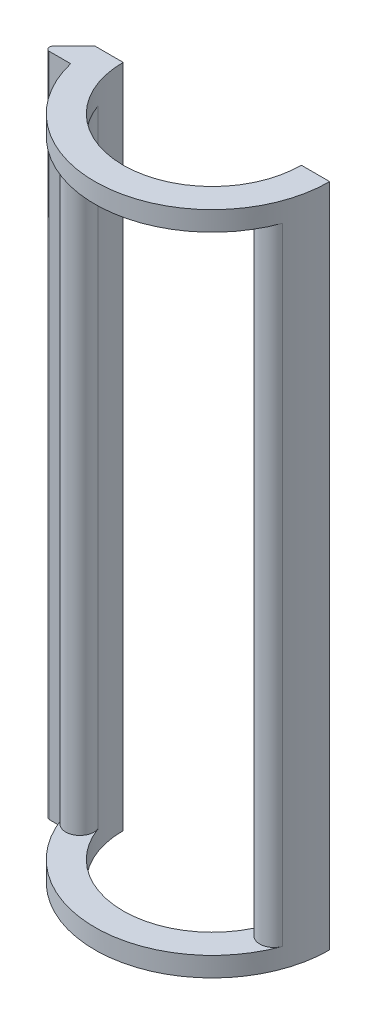
SolidWorks part; units mm, degrees
ref_plane "Front Plane" through (0, 0, 0) normal (0, 0, 1) x (1, 0, 0)
ref_plane "Top Plane" through (0, 0, 0) normal (0, 1, 0) x (1, 0, 0)
ref_plane "Right Plane" through (0, 0, 0) normal (1, 0, 0) x (0, 0, -1)
sketch "Sketch4" plane through (0, 0, 0) normal (0, 1, 0) x (1, 0, 0)
  line L0 (-28.9052, 0) -> (-38.1, 0)
  line L2 (-38.1, -8.89) -> (-46.99, -8.89)
  line L3 (-46.99, -8.89) -> (-38.1, 0)
  line L4 (28.9052, 0) -> (38.1, 0)
  line L5 (-38.1, -8.89) -> (-37.0483, -8.89)
  arc A0 (-28.9052, 0) -> (28.9052, 0) centre (0, 0) ccw
  arc A1 (38.1, 0) -> (-37.0483, -8.89) centre (0, 0) cw
  dimension "D1" = 57.8104
  dimension "D2" = 76.2
  dimension "D3" = 8.89
  dimension "D4" = 8.89
extrude "Boss-Extrude1" add sketch "Sketch4" along normal blind 215.9
fillet "Fillet2" radius 1.27 1 edges at (-46.99, 107.95, 8.89)
sketch "Sketch5" plane through (0, 0, 0) normal (0, 0, 1) x (1, 0, 0)
  line L0 (-37.0483, 215.9) -> (-37.0483, 0) construction
  line L1 (-24.3483, 6.35) -> (25.4, 6.35)
  line L2 (-24.3483, 6.35) -> (-24.3483, 209.55)
  line L3 (-24.3483, 209.55) -> (25.4, 209.55)
  line L4 (25.4, 6.35) -> (25.4, 209.55)
  line L5 (38.1, 215.9) -> (-37.0483, 215.9) construction
  line L6 (38.1, 215.9) -> (38.1, 0) construction
  line L7 (55, 0) -> (-55, 0) construction
  dimension "D1" = 12.7
  dimension "D2" = 6.35
  dimension "D3" = 12.7
  dimension "D4" = 6.35
sketch "Sketch6" plane through (0, 0, 0) normal (0, 1, 0) x (1, 0, 0)
  line L0 (0, 0) -> (-48.3523, -17.5988) construction
  line L1 (0, 0) -> (55.3566, -20.1481) construction
  line L2 (0, -55) -> (0, 55) construction
  circle A0 centre (0, 0) radius 38.1 construction
  arc A1 (-35.8023, -13.031) -> (35.8023, -13.031) centre (0, 0) ccw
  arc A2 (27.162, -9.8862) -> (-27.162, -9.8862) centre (0, 0) cw
  arc A3 (-28.9052, 0) -> (28.9052, 0) centre (0, 0) ccw construction
  arc A4 (-35.8023, -13.031) -> (-27.162, -9.8862) centre (-31.4821, -11.4586) ccw
  arc A5 (35.8023, -13.031) -> (27.162, -9.8862) centre (31.4821, -11.4586) cw
  dimension "D1" = 70
  dimension "D2" = 70
extrude "Cut-Extrude2" cut sketch "Sketch6" along normal blind 203.2 from offset 6.35
